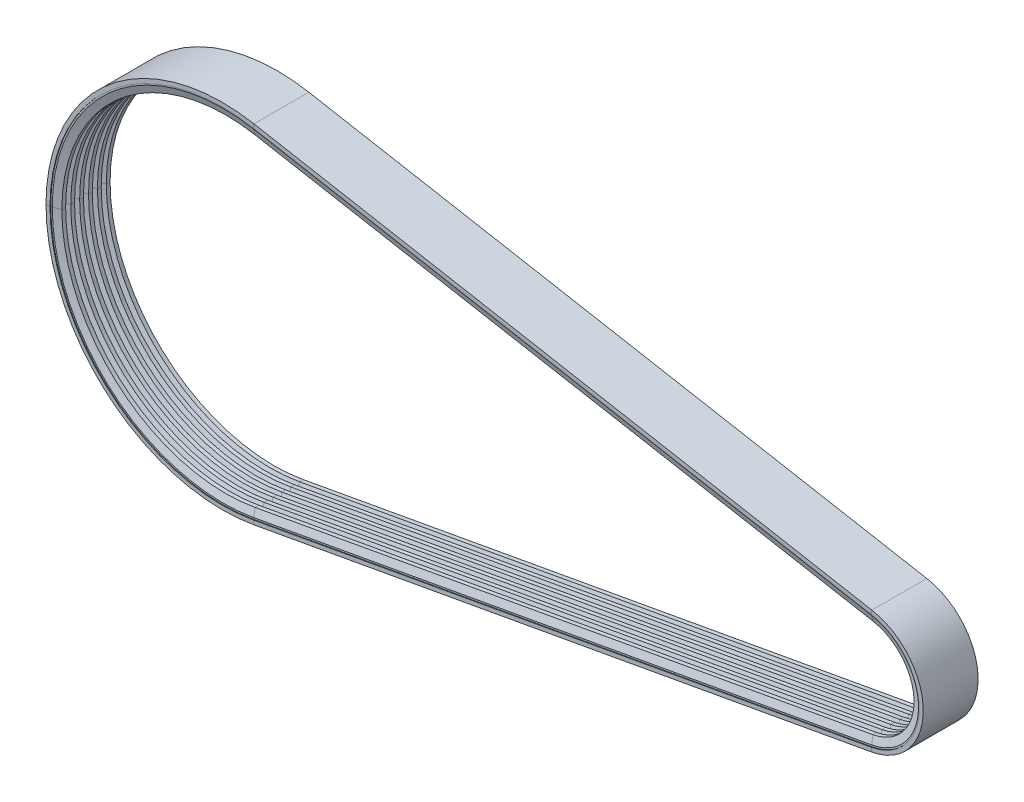
SolidWorks part; units mm, degrees
material "Эпихлоргидрин"
ref_plane "Спереди" through (0, 0, 0) normal (0, 0, 1) x (1, 0, 0)
ref_plane "Сверху" through (0, 0, 0) normal (0, 1, 0) x (1, 0, 0)
ref_plane "Справа" through (0, 0, 0) normal (1, 0, 0) x (0, 0, -1)
sketch "Эскиз1" plane through (0, 0, 0) normal (0, 0, 1) x (1, 0, 0)
  line L0 (-350.1512, 0) -> (178.9762, 0) construction
  line L1 (-159.9643, 44.2767) -> (2.6786, 14.7589)
  line L2 (-159.9643, -44.2767) -> (2.6786, -14.7589)
  arc A0 (2.6786, -14.7589) -> (2.6786, 14.7589) centre (0, 0) ccw
  arc A1 (-159.9643, 44.2767) -> (-159.9643, -44.2767) centre (-168, 0) ccw
  dimension "D1" = 30
  dimension "D2" = 90
  dimension "D3" = 168
sketch "Эскиз2" plane through (0, 0, 0) normal (0, 1, 0) x (1, 0, 0)
  line L1 (-213, -15.8075) -> (-213, 15.8075) construction
  line L8 (-214.25, 15.8075) -> (-214.25, -15.8075) construction
  line L10 (-213, 0) -> (-207.8766, 0) construction
  line L11 (-207.8766, 2.34) -> (-200.8, 2.34) construction
  line L12 (-207.8766, 4.68) -> (-201.255, 4.68) construction
  line L14 (-213, 0) -> (-211.15, 0.6733)
  line L27 (-213, 0) -> (-211.15, -0.6733)
  line L28 (0, 0) -> (-213, 0) construction
  line L29 (-350.1512, 0) -> (178.9762, 0) construction
  line L30 (-211.15, 1.6667) -> (-213, 2.34)
  line L31 (-213, 2.34) -> (-211.15, 3.0133)
  line L32 (-195.2943, 7.02) -> (-230.7057, 7.02) construction
  line L33 (-210.4943, 9.36) -> (-182.2848, 9.36) construction
  line L34 (-211.15, 4.0067) -> (-213, 4.68)
  line L35 (-213, 4.68) -> (-211.15, 5.3533)
  line L36 (-211.15, 6.3467) -> (-213, 7.02)
  line L37 (-211.0947, -2.34) -> (-184.2958, -2.34) construction
  line L38 (-208.7223, -4.68) -> (-188.4058, -4.68) construction
  line L39 (-207.8766, -7.02) -> (-188.9405, -7.02) construction
  line L40 (-211.15, -1.6667) -> (-213, -2.34)
  line L41 (-213, -2.34) -> (-211.15, -3.0133)
  line L42 (-211.15, -4.0067) -> (-213, -4.68)
  line L43 (-213, -4.68) -> (-211.15, -5.3533)
  line L44 (-211.15, -6.3467) -> (-213, -7.02)
  line L48 (-213, -7.02) -> (-213.4, -7.02)
  line L49 (-213.4, -7.02) -> (-213.4, -7.22)
  line L50 (-213.4, -7.22) -> (-214.45, -7.22)
  line L51 (-214.45, -7.22) -> (-214.45, 7.22)
  line L52 (-214.45, 7.22) -> (-213.4, 7.22)
  line L53 (-213.4, 7.22) -> (-213.4, 7.02)
  line L54 (-213.4, 7.02) -> (-213, 7.02)
  line L55 (-211.15, 4.0067) -> (-211.15, 3.0133)
  line L56 (-211.15, 6.3467) -> (-211.15, 5.3533)
  line L57 (-211.15, 1.6667) -> (-211.15, 0.6733)
  line L58 (-211.15, -0.6733) -> (-211.15, -1.6667)
  line L59 (-211.15, -3.0133) -> (-211.15, -4.0067)
  line L60 (-211.15, -5.3533) -> (-211.15, -6.3467)
  line L62 (-213, 0) -> (-159.9643, 0) construction
  line L63 (-213, 0) -> (-159.9643, 0) construction
  point P3 (-213, 0)
  dimension "D6" = 20
  dimension "D10" = 2.34
  dimension "D14" = 0.4
  dimension "D18" = 3.3
  dimension "D1" = 1.25
  dimension "D3" = 2.34
  dimension "D4" = 2.34
  dimension "D5" = 20
  dimension "D7" = 20
  dimension "D8" = 2.34
  dimension "D9" = 2.34
  dimension "D11" = 2.34
  dimension "D12" = 2.34
  dimension "D13" = 0.4
  dimension "D15" = 0.2
  dimension "D16" = 0.2
  dimension "D17" = 1.85
sweep "По траектории1" add profiles "Эскиз2" path "Эскиз1"
sketch "Эскиз3" plane through (0, 0, 0) normal (0, 0, 1) x (1, 0, 0)
  line L0 (0, 0) -> (-180, 0) construction
  circle A0 centre (0, 0) radius 20
  circle A1 centre (-180, 0) radius 40
  dimension "D1" = 80
  dimension "D2" = 40
  dimension "D3" = 180
